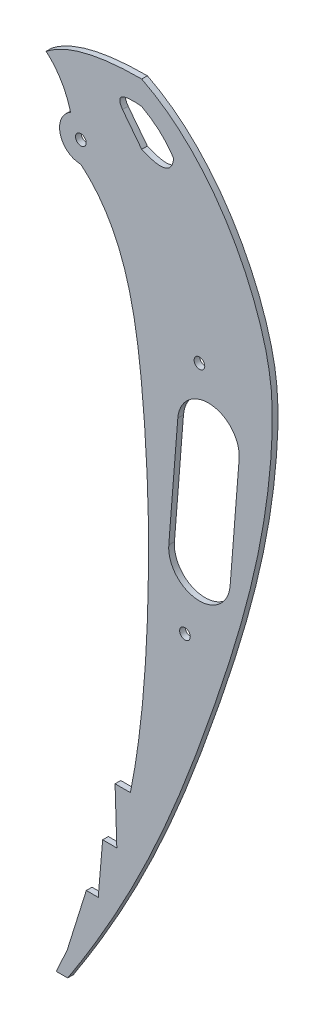
SolidWorks part; units mm, degrees
ref_plane "Front Plane" through (0, 0, 0) normal (0, 0, 1) x (1, 0, 0)
ref_plane "Top Plane" through (0, 0, 0) normal (0, 1, 0) x (1, 0, 0)
ref_plane "Right Plane" through (0, 0, 0) normal (1, 0, 0) x (0, 0, -1)
sketch "Sketch1" plane through (0, 0, 0) normal (0, 0, 1) x (1, 0, 0)
  line L0 (0, 0) -> (0, -230) construction
  line L1 (-2456.8724, -2628.928) -> (-1390.2057, -2628.928) construction
  line L2 (-20.8748, -230) -> (-24.1076, -230)
  line L3 (-3.187, -175.8819) -> (-7.516, -175.8819)
  line L4 (-7.516, -175.8819) -> (-7.0201, -191.3116)
  line L5 (-7.0201, -191.3116) -> (-11.0217, -191.3116)
  line L6 (-11.0217, -191.3116) -> (-12.259, -205.9939)
  line L7 (-12.259, -205.9939) -> (-15.623, -205.9939)
  line L8 (-15.623, -205.9939) -> (-21.0272, -223.2829)
  line L9 (-21.0272, -223.2829) -> (-24.1076, -230)
  line L10 (18.8312, -78.3893) -> (16.2802, -110.6552) construction
  line L11 (27.4792, -79.0731) -> (24.9281, -111.339)
  line L12 (10.1832, -77.7056) -> (7.6322, -109.9715)
  arc A0 (-20.053, -18.1595) -> (-17.1603, -29.4162) centre (-17.1603, -23.4162) ccw
  circle A1 centre (-17.1603, -23.4162) radius 1.5
  arc A2 (27.4792, -79.0731) -> (10.1832, -77.7056) centre (18.8312, -78.3893) ccw
  circle A3 centre (16.2802, -61.2395) radius 1.5
  arc A4 (7.6322, -109.9715) -> (24.9281, -111.339) centre (16.2802, -110.6552) ccw
  circle A5 centre (12.1935, -129.3981) radius 1.5
  spline S0 degree 3 poles (-17.1603, -29.4162) (-8.3984, -36.7335) (-2.5716, -52.9687) (0.6611, -79.1111) (2.2051, -105.0546) (1.8378, -131.716) (0.1379, -155.634) (-1.7719, -168.8677) (-3.187, -175.8819) knots 0 0 0 0 0.158482 0.23721 0.379018 0.53054 0.619678 0.722684 0.722684 0.722684 0.722684
  spline S1 degree 3 poles (0, 0) (20.4596, -10.2122) (34.5663, -39.2317) (36.9931, -61.4677) (36.2264, -93.4939) (19.7598, -148.8717) (-0.7648, -199.1592) (-20.8748, -230) knots 0 0 0 0 0.214563 0.244194 0.296302 0.633937 1 1 1 1
  spline S2 degree 2 poles (0, 0) (-18.4134, 0.0165) (-26.9697, -6.7163) knots 0 0 0 1 1 1
  spline S3 degree 2 poles (-20.053, -18.1595) (-21.8936, -11.0672) (-26.9697, -6.7163) knots 0 0 0 1 1 1
  spline S8 degree 2 poles (0, -6.7163) (5.912, -9.9495) (8.987, -14.881) knots 0 0 0 1 1 1
  spline S9 degree 2 poles (-5.4194, -10.1625) (-1.882, -14.5842) (0, -17.1688) knots 0 0 0 1 1 1
  spline S10 degree 2 poles (0, -17.1688) (8.4155, -20.921) (8.987, -14.881) knots 0 0 0 1 1 1
  spline S11 degree 2 poles (-5.4194, -10.1625) (-8.3828, -5.8408) (0, -6.7163) knots 0 0 0 1 1 1
  point P33 (17.5557, -94.5223)
  dimension "D1" = 12
  dimension "D2" = 3
  dimension "D5" = 3
  dimension "D7" = 3
  dimension "D3" = 230
extrude "Boss-Extrude1" add sketch "Sketch1" along normal blind 1.6
